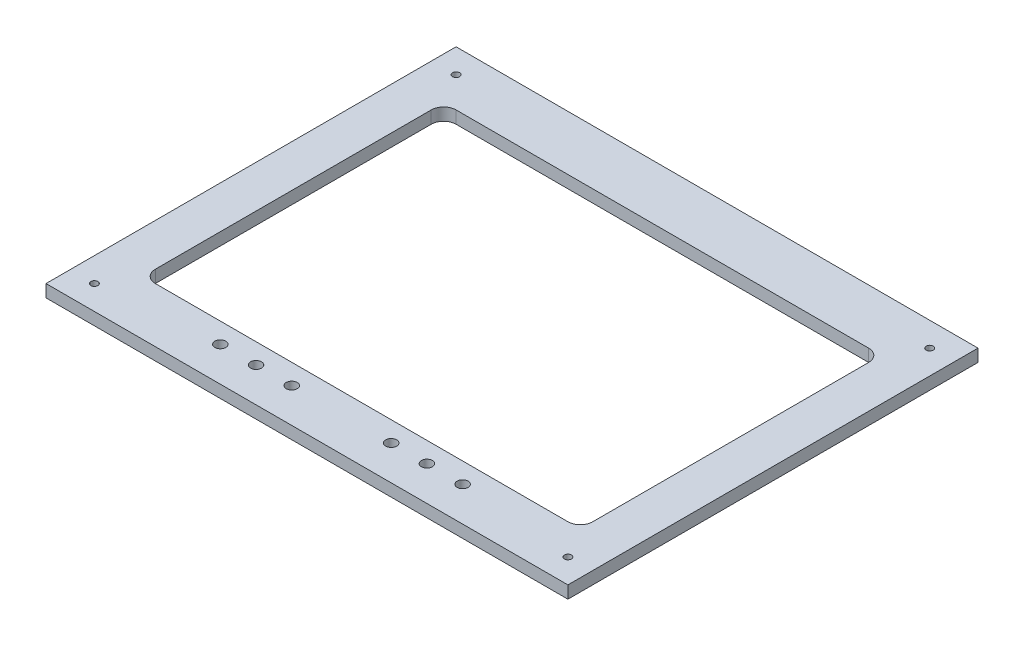
SolidWorks part; units mm, degrees
material "Acrylic (Medium-high impact)"
ref_plane "Front Plane" through (0, 0, 0) normal (0, 0, 1) x (1, 0, 0)
ref_plane "Top Plane" through (0, 0, 0) normal (0, 1, 0) x (1, 0, 0)
ref_plane "Right Plane" through (0, 0, 0) normal (1, 0, 0) x (0, 0, -1)
sketch "Sketch1" plane through (0, 0, 0) normal (0, 1, 0) x (1, 0, 0)
  line L1 (-133.35, 104.775) -> (133.35, 104.775)
  line L2 (-133.35, 104.775) -> (-133.35, -104.775)
  line L3 (-133.35, -104.775) -> (133.35, -104.775)
  line L4 (133.35, 104.775) -> (133.35, -104.775)
  line L5 (-133.35, 104.775) -> (133.35, -104.775) construction
  line L6 (-133.35, -104.775) -> (133.35, 104.775) construction
  point P0 (0, 0)
  dimension "D1" = 209.55
  dimension "D2" = 266.7
extrude "Boss-Extrude1" add sketch "Sketch1" along normal blind 6.35
hole_wizard "M3 Clearance Hole1" positions "Sketch2" profile "Sketch3" hole size "M3" standard "ANSI Metric" end condition through all
sketch "Sketch2" plane through (0, 6.35, 0) normal (0, 1, 0) x (1, 0, 0)
  line L0 (-133.35, -104.775) -> (133.35, -104.775) construction
  line L1 (133.35, -104.775) -> (133.35, 104.775) construction
  line L2 (133.35, 104.775) -> (-133.35, 104.775) construction
  line L3 (-133.35, 104.775) -> (-133.35, -104.775) construction
  point P0 (121.0056, -92.4306)
  point P2 (-121.0056, -92.4306)
  point P4 (-121.0056, 92.4306)
  point P6 (121.0056, 92.4306)
  dimension "D1" = 12.3444
  dimension "D2" = 12.3444
  dimension "D3" = 12.3444
  dimension "D4" = 12.3444
sketch "Sketch3" plane through (121.0056, 6.35, 92.4306) normal (1, 0, 0) x (0, 0, 1)
  line L0 (0, 0) -> (0, 6.35)
  line L1 (0, 6.35) -> (1.8, 6.35)
  line L2 (1.8, 6.35) -> (1.8, 0)
  line L5 (1.8, 0) -> (0, 0)
  line L11 (0, -6.35) -> (0, 107.95) construction
  dimension "Thru Hole Dia." = 3.6
  dimension "Thru Hole Depth" = 6.35
sketch "Sketch4" plane through (0, 6.35, 0) normal (0, 1, 0) x (1, 0, 0)
  line L0 (-133.35, 104.775) -> (-133.35, -104.775) construction
  line L1 (111.76, -76.835) -> (-111.76, -76.835)
  line L2 (111.76, -76.835) -> (111.76, 76.835)
  line L3 (111.76, 76.835) -> (-111.76, 76.835)
  line L4 (-111.76, -76.835) -> (-111.76, 76.835)
  line L5 (111.76, -76.835) -> (-111.76, 76.835) construction
  line L6 (111.76, 76.835) -> (-111.76, -76.835) construction
  line L7 (133.35, 104.775) -> (-133.35, 104.775) construction
  point P0 (0, 0)
  dimension "D1" = 21.59
  dimension "D2" = 27.94
extrude "Cut-Extrude1" cut sketch "Sketch4" against normal through all
hole_wizard "#10 Clearance Hole1" positions "Sketch5" profile "Sketch6" hole size "#10" standard "ANSI Inch" end condition through all
sketch "Sketch5" plane through (0, 6.35, 0) normal (0, 1, 0) x (1, 0, 0)
  line L0 (-61.9125, -87.1474) -> (-25.4, -87.1474) construction
  line L2 (25.4, -87.1474) -> (61.9125, -87.1474) construction
  line L4 (-25.4, -87.1474) -> (25.4, -87.1474) construction
  line L5 (-111.76, -76.835) -> (111.76, -76.835) construction
  point P0 (-61.9125, -87.1474)
  point P2 (-43.6562, -87.1474)
  point P4 (-25.4, -87.1474)
  point P6 (25.4, -87.1474)
  point P8 (43.6562, -87.1474)
  point P10 (61.9125, -87.1474)
  point P22 (43.6562, -87.1474)
  point P23 (-43.6562, -87.1474)
  point P29 (0, -87.1474)
  dimension "D1" = 36.5125
  dimension "D2" = 36.5125
  dimension "D3" = 50.8
  dimension "D4" = 10.3124
sketch "Sketch6" plane through (-61.9125, 6.35, 87.1474) normal (1, 0, 0) x (0, 0, 1)
  line L0 (0, 0) -> (0, 6.35)
  line L1 (0, 6.35) -> (2.8067, 6.35)
  line L2 (2.8067, 6.35) -> (2.8067, 0)
  line L5 (2.8067, 0) -> (0, 0)
  line L11 (0, -6.35) -> (0, 107.95) construction
  dimension "Thru Hole Dia." = 5.6134
  dimension "Thru Hole Depth" = 6.35
fillet "Fillet1" radius 6.35 4 edges at (111.76, 3.175, -76.835) (111.76, 3.175, 76.835) (-111.76, 3.175, 76.835) (-111.76, 3.175, -76.835)
